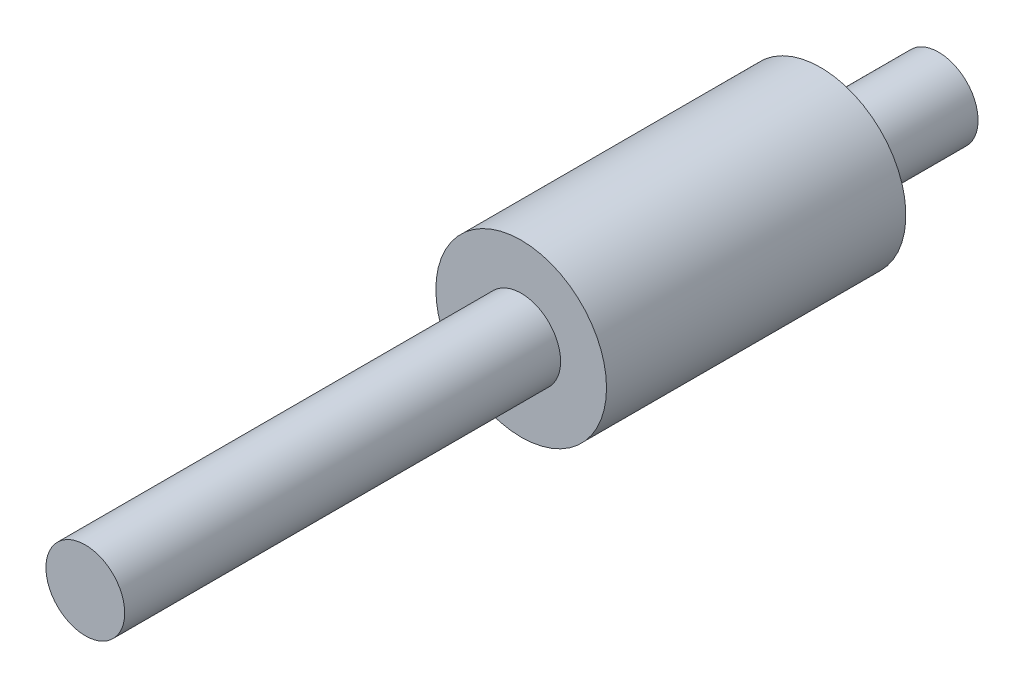
SolidWorks part; units mm, degrees
ref_plane "Front Plane" through (0, 0, 0) normal (0, 0, 1) x (1, 0, 0)
ref_plane "Top Plane" through (0, 0, 0) normal (0, 1, 0) x (1, 0, 0)
ref_plane "Right Plane" through (0, 0, 0) normal (1, 0, 0) x (0, 0, -1)
sketch "Sketch1" plane through (0, 0, 0) normal (0, 0, 1) x (1, 0, 0)
  circle A0 centre (0, 0) radius 6.5
  dimension "D1" = 13
extrude "Boss-Extrude1" add sketch "Sketch1" along normal blind 65
ref_plane "Plane1" through (0, 0, 32.5) normal (0, 0, 1) x (1, 0, 0)
sketch "Sketch3" plane through (0, 0, 65) normal (0, 0, 1) x (1, 0, 0)
  circle A0 centre (0, 0) radius 3
  circle A1 centre (0, 0) radius 6.5
  dimension "D1" = 6
  dimension "D2" = 13
extrude "Cut-Extrude2" cut sketch "Sketch3" against normal blind 33.2
sketch "Sketch4" plane through (0, 0, 0) normal (0, 0, -1) x (-1, 0, 0)
  circle A0 centre (0, 0) radius 3
  circle A1 centre (0, 0) radius 6.5 construction
  circle A2 centre (0, 0) radius 6.5
  dimension "D1" = 6
extrude "Cut-Extrude3" cut sketch "Sketch4" against normal blind 9
